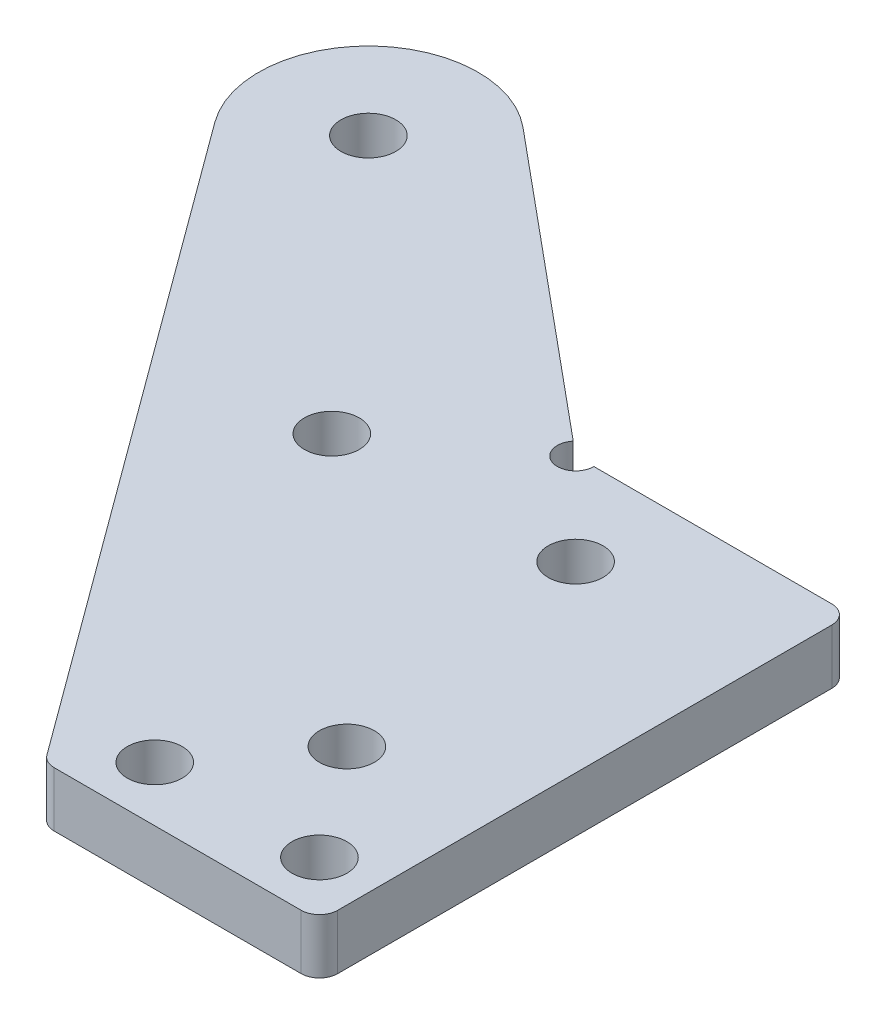
SolidWorks part; units mm, degrees
material "Thornel Mat VMA"
ref_plane "前视基准面" through (0, 0, 0) normal (0, 0, 1) x (1, 0, 0)
ref_plane "上视基准面" through (0, 0, 0) normal (0, 1, 0) x (1, 0, 0)
ref_plane "右视基准面" through (0, 0, 0) normal (1, 0, 0) x (0, 0, -1)
sketch "草图4" plane through (0, 0, 0) normal (0, 1, 0) x (1, 0, 0)
  line L0 (164.6838, -11.5) -> (-164.6838, -11.5) construction
  line L1 (-106, 0) -> (106, 0) construction
  line L2 (-106, 0) -> (-182.5441, -15) construction
  line L3 (-182.5441, -15) -> (-197.2641, -17.8846) construction
  line L4 (-197.2641, -17.8846) -> (-203.5141, 14.0088) construction
  line L5 (-203.5141, 14.0088) -> (-111.8251, 50) construction
  line L6 (-111.8251, 50) -> (-106, 0) construction
  line L7 (0, -1.65) -> (0, 1.65) construction
  line L8 (111.8251, 50) -> (106, 0) construction
  line L9 (203.5141, 14.0088) -> (111.8251, 50) construction
  line L10 (197.2641, -17.8846) -> (203.5141, 14.0088) construction
  line L11 (182.5441, -15) -> (197.2641, -17.8846) construction
  line L12 (106, 0) -> (182.5441, -15) construction
  line L13 (-276.4201, -167.5536) -> (-38.1004, -11.5) construction
  line L14 (-38.1004, -11.5) -> (71.4621, -178.8202) construction
  line L15 (71.4621, -178.8202) -> (312.9419, -20.6974) construction
  line L16 (-320.7866, -134.5959) -> (102.1638, -11.5) construction
  line L17 (102.1638, -11.5) -> (158.0531, -203.5323) construction
  line L18 (158.0531, -203.5323) -> (333.4296, -152.4905) construction
  line L19 (-288.3145, -150.6671) -> (0, -11.5) construction
  line L20 (0, -11.5) -> (253.3874, -133.8081) construction
  line L21 (-486.9635, 108.8) -> (-486.9635, -91.2) construction
  line L22 (-486.9635, -91.2) -> (-206.9635, -91.2) construction
  line L23 (-206.9635, -91.2) -> (-486.9635, 108.8) construction
  circle A0 centre (-182.5441, -15) radius 76.2
  circle A1 centre (182.5441, -15) radius 76.2
  dimension "D6" = 152.4
  dimension "D1" = 11.5
  dimension "D2" = 212
  dimension "D3" = 78
  dimension "D4" = 15
  dimension "D5" = 32.5
  dimension "D7" = 98.5
  dimension "D8" = 15
  dimension "D9" = 50
  dimension "D10" = 200
  dimension "D11" = 128.468
  dimension "D12" = 280
  dimension "D13" = 200
sketch "草图1" plane through (0, 0, 0) normal (0, 1, 0) x (1, 0, 0)
  line L8 (-107.991, 54.6152) -> (-91, 40.5)
  line L19 (-76, 40.5) -> (-76, 11.5)
  line L20 (-91, 40.5) -> (-76, 40.5)
  line L23 (-76, 11.5) -> (-91, 11.5)
  line L25 (-88, 14.5) -> (-79, 14.5) construction
  line L28 (-83.5, 11.5) -> (-83.5, 20.5) construction
  line L29 (-116.6614, 46.4489) -> (-91, 11.5)
  line L32 (-91, 11.5) -> (-91, 40.5) construction
  line L33 (-111.8251, 50) -> (-91, 26) construction
  circle A1 centre (-111.8251, 50) radius 1.5
  arc A2 (-107.991, 54.6152) -> (-116.6614, 46.4489) centre (-111.8251, 50) ccw
  circle A5 centre (-88, 14.5) radius 1.5
  circle A6 centre (-79, 14.5) radius 1.5
  circle A7 centre (-83.5, 20.5) radius 1.5
  circle A8 centre (-86, 35.5) radius 1.5
  circle A9 centre (-98.7175, 34.894) radius 1.5
  point P13 (-83.5, 14.5)
  dimension "D4" = 9
  dimension "D8" = 3
  dimension "D9" = 10
  dimension "D10" = 5
  dimension "D12" = 6
  dimension "D2" = 15
  dimension "D5" = 3
  dimension "D11" = 3
  dimension "D13" = 20
  dimension "D3" = 9
  dimension "D6" = 3
  dimension "D7" = 29
  dimension "D14" = 11.5
  dimension "D15" = 30
extrude "凸台-拉伸1" add sketch "草图1" along normal blind 3
sketch "草图2" [suppressed] plane through (0, 4, 0) normal (0, 1, 0) x (1, 0, 0)
  circle A0 centre (-127, 55) radius 2
  circle A1 centre (-110, 30) radius 2
  circle A4 centre (-95, 0) radius 10.75 construction
  dimension "D1" = 4
  dimension "D2" = 30
  dimension "D6" = 55
  dimension "D5" = 32
  dimension "8" = 15
extrude "切除-拉伸1" [suppressed] cut sketch "草图2" against normal through all
sketch "草图3" plane through (0, 3, 0) normal (0, 1, 0) x (1, 0, 0)
  circle A4 centre (-91, 40.5) radius 1
  dimension "D1" = 2
extrude "切除-拉伸2" cut sketch "草图3" against normal through all
fillet "圆角1" radius 1 3 edges at (-91, 1.5, -11.5) (-76, 1.5, -11.5) (-76, 1.5, -40.5)
